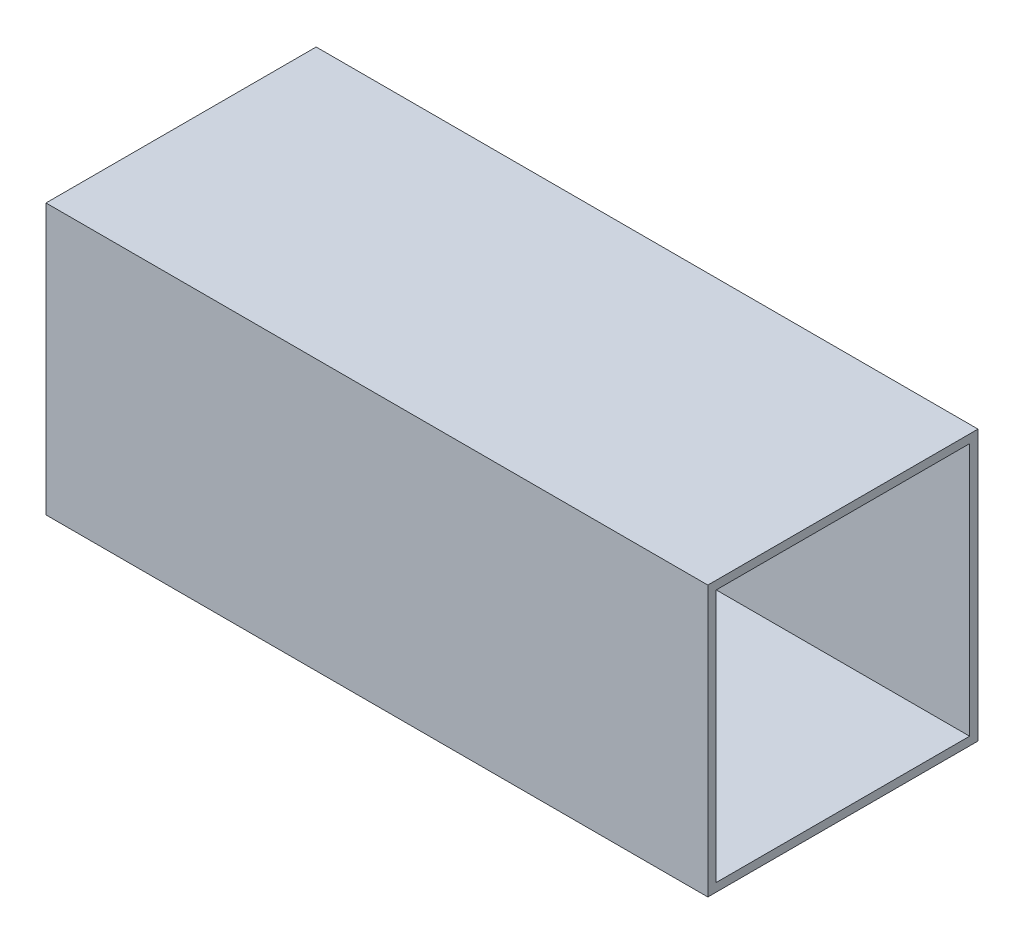
SolidWorks part; units mm, degrees
ref_plane "Alzado" through (0, 0, 0) normal (0, 0, 1) x (1, 0, 0)
ref_plane "Planta" through (0, 0, 0) normal (0, 1, 0) x (1, 0, 0)
ref_plane "Vista lateral" through (0, 0, 0) normal (1, 0, 0) x (0, 0, -1)
sketch "Croquis1" plane through (0, 0, 0) normal (0, 0, 1) x (1, 0, 0)
  line L0 (0, 0) -> (70, 0)
  dimension "D1" = 70
other "Al tube (square) 1.125 SQ X .035 WALL(3)"
ref_plane "Plano1" through (0, 0, 0) normal (1, 0, 0) x (0, 1, 0)
sketch "Sketch11" plane through (0, 0, 0) normal (1, 0, 0) x (0, 1, 0)
  line L0 (-13.3985, -13.3985) -> (-13.3985, 13.3985)
  line L1 (13.3985, 13.3985) -> (-13.3985, 13.3985)
  line L2 (13.3985, 13.3985) -> (13.3985, -13.3985)
  line L3 (-13.3985, -13.3985) -> (13.3985, -13.3985)
  line L4 (-14.2875, -14.2875) -> (14.2875, -14.2875)
  line L5 (-14.2875, -14.2875) -> (-14.2875, 14.2875)
  line L6 (14.2875, 14.2875) -> (-14.2875, 14.2875)
  line L7 (14.2875, 14.2875) -> (14.2875, -14.2875)
  line L8 (0, -13.3985) -> (0, -14.2875) construction
  line L9 (0, -13.3985) -> (0, 13.3985) construction
  line L10 (0, 13.3985) -> (0, 14.2875) construction
  line L11 (14.2875, 0) -> (13.3985, 0) construction
  line L12 (13.3985, 0) -> (-13.3985, 0) construction
  line L13 (-13.3985, 0) -> (-14.2875, 0) construction
  point P14 (0, 0)
  dimension "Thickness" = 0.889
  dimension "V_leg" = 28.575
  dimension "H_leg" = 28.575
